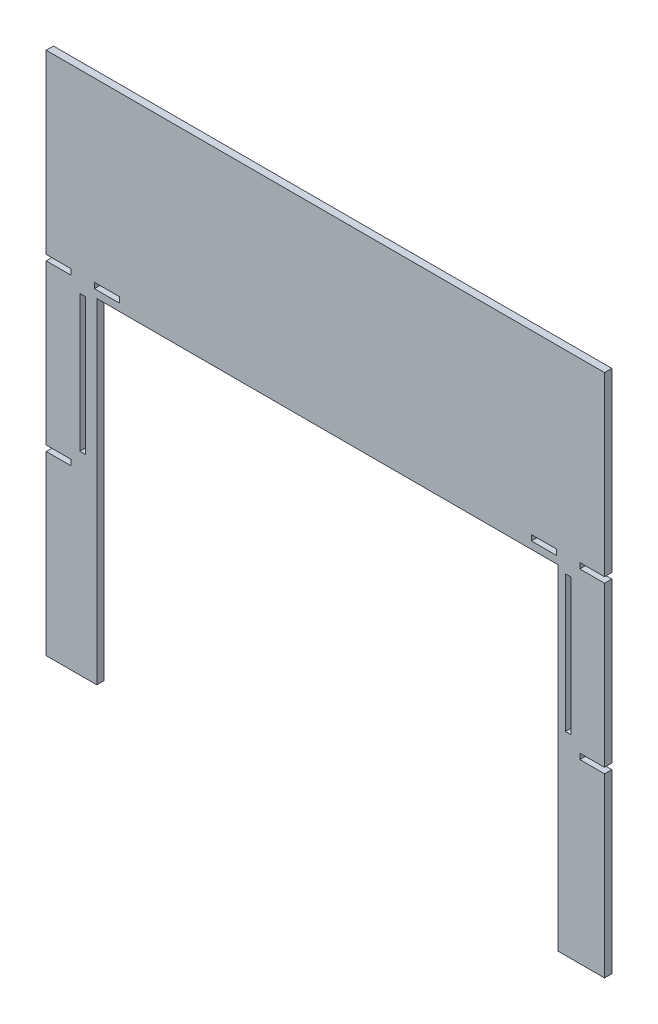
SolidWorks part; units mm, degrees
ref_plane "Front Plane" through (0, 0, 0) normal (0, 0, 1) x (1, 0, 0)
ref_plane "Top Plane" through (0, 0, 0) normal (0, 1, 0) x (1, 0, 0)
ref_plane "Right Plane" through (0, 0, 0) normal (1, 0, 0) x (0, 0, -1)
sketch "Sketch2" plane through (0, 0, 184) normal (0, 0, 1) x (1, 0, 0)
  line L2 (-172.5, -108) -> (57.5, -108)
  line L3 (-172.5, -108) -> (-172.5, 108)
  line L4 (-172.5, 108) -> (57.5, 108)
  line L5 (57.5, -108) -> (57.5, 108)
  line L6 (-172.5, -108) -> (57.5, 108) construction
  line L7 (-172.5, 108) -> (57.5, -108) construction
  point P2 (-57.5, 0)
extrude "Boss-Extrude1" add sketch "Sketch2" along normal blind 3
sketch "Sketch5" plane through (0, 0, 187) normal (0, 0, 1) x (1, 0, 0)
  line L0 (38.35, -108) -> (38.35, 29.85)
  line L1 (38.35, 29.85) -> (-151.65, 29.85)
  line L2 (-172.5, -108) -> (57.5, -108) construction
  line L3 (47.5, -33) -> (47.5, -35) construction
  line L4 (47.5, -35) -> (57.5, -35) construction
  line L5 (57.5, -35) -> (57.5, -33) construction
  line L6 (57.5, -33) -> (47.5, -33) construction
  line L7 (41.5, -28) -> (43.5, -28)
  line L9 (-151.65, 29.85) -> (-151.65, -108)
  line L10 (-151.65, -108) -> (38.35, -108)
  line L12 (43.5, -28) -> (43.5, 28)
  line L13 (43.5, 28) -> (41.5, 28)
  line L14 (41.5, 28) -> (41.5, -28)
  line L15 (41.5, -28) -> (43.5, -28) construction
  line L16 (43.5, -28) -> (43.5, 28) construction
  line L17 (43.5, 28) -> (41.5, 28) construction
  line L18 (41.5, 28) -> (41.5, -28) construction
  line L37 (47.5, 35) -> (47.5, 33) construction
  line L39 (47.5, 33) -> (57.5, 33) construction
  line L57 (57.5, 33) -> (57.5, 35) construction
  line L65 (57.5, 35) -> (47.5, 35) construction
  line L70 (37.5, 33) -> (37.5, 35) construction
  line L71 (37.5, 35) -> (27.5, 35) construction
  line L72 (27.5, 35) -> (27.5, 33) construction
  line L73 (27.5, 33) -> (37.5, 33) construction
  line L78 (47.5, -33) -> (47.5, -35) construction
  line L79 (47.5, -35) -> (57.5, -35) construction
  line L81 (57.5, -35) -> (57.5, -33) construction
  line L134 (57.5, -33) -> (47.5, -33) construction
  line L135 (47.5, 35) -> (47.5, 33) construction
  line L136 (47.5, 33) -> (57.5, 33) construction
  line L137 (57.5, 33) -> (57.5, 35) construction
  line L138 (57.5, 35) -> (47.5, 35) construction
  line L139 (37.5, 33) -> (37.5, 35) construction
  line L140 (37.5, 35) -> (27.5, 35) construction
  line L141 (27.5, 35) -> (27.5, 33) construction
  line L142 (27.5, 33) -> (37.5, 33) construction
  line L144 (37.65, 32.85) -> (37.65, 35.15)
  line L146 (37.65, 35.15) -> (27.35, 35.15)
  line L147 (27.35, 35.15) -> (27.35, 32.85)
  line L148 (27.35, 32.85) -> (37.65, 32.85)
  line L149 (47.35, 35.15) -> (47.35, 32.85)
  line L150 (47.35, 32.85) -> (57.65, 32.85)
  line L151 (57.65, 32.85) -> (57.65, 35.15)
  line L152 (57.65, 35.15) -> (47.35, 35.15)
  line L153 (41.35, -28.15) -> (43.65, -28.15)
  line L154 (43.65, -28.15) -> (43.65, 28.15)
  line L155 (43.65, 28.15) -> (41.35, 28.15)
  line L156 (41.35, 28.15) -> (41.35, -28.15)
  line L157 (47.35, -32.85) -> (47.35, -35.15)
  line L158 (47.35, -35.15) -> (57.65, -35.15)
  line L159 (57.65, -35.15) -> (57.65, -32.85)
  line L160 (57.65, -32.85) -> (47.35, -32.85)
  line L161 (-158.5, -28) -> (-156.5, -28) construction
  line L162 (-156.5, 28) -> (-158.5, 28) construction
  line L163 (-158.5, 28) -> (-158.5, -28) construction
  line L164 (-156.5, -28) -> (-156.5, 28) construction
  line L165 (-158.5, -28) -> (-156.5, -28) construction
  line L166 (-156.5, 28) -> (-158.5, 28) construction
  line L167 (-158.5, 28) -> (-158.5, -28) construction
  line L168 (-156.5, -28) -> (-156.5, 28) construction
  line L169 (-172.5, 33) -> (-162.5, 33) construction
  line L170 (-162.5, 33) -> (-162.5, 35) construction
  line L171 (-162.5, 35) -> (-172.5, 35) construction
  line L172 (-172.5, 33) -> (-162.5, 33) construction
  line L173 (-162.5, 33) -> (-162.5, 35) construction
  line L174 (-162.5, 35) -> (-172.5, 35) construction
  line L175 (-142.5, 33) -> (-142.5, 35) construction
  line L176 (-152.5, 35) -> (-152.5, 33) construction
  line L177 (-152.5, 33) -> (-142.5, 33) construction
  line L178 (-142.5, 35) -> (-152.5, 35) construction
  line L179 (-142.5, 33) -> (-142.5, 35) construction
  line L180 (-142.5, 35) -> (-152.5, 35) construction
  line L181 (-152.5, 35) -> (-152.5, 33) construction
  line L182 (-152.5, 33) -> (-142.5, 33) construction
  line L183 (-172.5, -33) -> (-172.5, -35) construction
  line L184 (-172.5, -35) -> (-162.5, -35) construction
  line L185 (-162.5, -35) -> (-162.5, -33) construction
  line L186 (-162.5, -33) -> (-172.5, -33) construction
  line L187 (-172.5, -33) -> (-172.5, -35) construction
  line L188 (-172.5, -35) -> (-162.5, -35) construction
  line L189 (-162.5, -35) -> (-162.5, -33) construction
  line L190 (-162.5, -33) -> (-172.5, -33) construction
  line L191 (-172.5, 35) -> (-172.5, 33) construction
  line L192 (-172.5, 35) -> (-172.5, 33) construction
  line L193 (-158.65, -28.15) -> (-156.35, -28.15)
  line L194 (-156.35, -28.15) -> (-156.35, 28.15)
  line L195 (-156.35, 28.15) -> (-158.65, 28.15)
  line L196 (-158.65, 28.15) -> (-158.65, -28.15)
  line L197 (-142.35, 32.85) -> (-142.35, 35.15)
  line L198 (-142.35, 35.15) -> (-152.65, 35.15)
  line L199 (-152.65, 35.15) -> (-152.65, 32.85)
  line L200 (-152.65, 32.85) -> (-142.35, 32.85)
  line L201 (-172.65, 35.15) -> (-172.65, 32.85)
  line L202 (-172.65, 32.85) -> (-162.35, 32.85)
  line L203 (-162.35, 32.85) -> (-162.35, 35.15)
  line L204 (-162.35, 35.15) -> (-172.65, 35.15)
  line L205 (-172.65, -32.85) -> (-172.65, -35.15)
  line L206 (-172.65, -35.15) -> (-162.35, -35.15)
  line L207 (-162.35, -35.15) -> (-162.35, -32.85)
  line L208 (-162.35, -32.85) -> (-172.65, -32.85)
  dimension "D5" = 190
  dimension "D4" = 3
  dimension "D6" = 3
  dimension "D1" = 0
  dimension "D2" = 0.15
  dimension "D3" = 0.15
extrude "Cut-Extrude3" cut sketch "Sketch5" against normal blind 3
equation "\"HoleOpeningWidth\"=190"
equation "\"D5@Sketch5\"=\"HoleOpeningWidth\""
